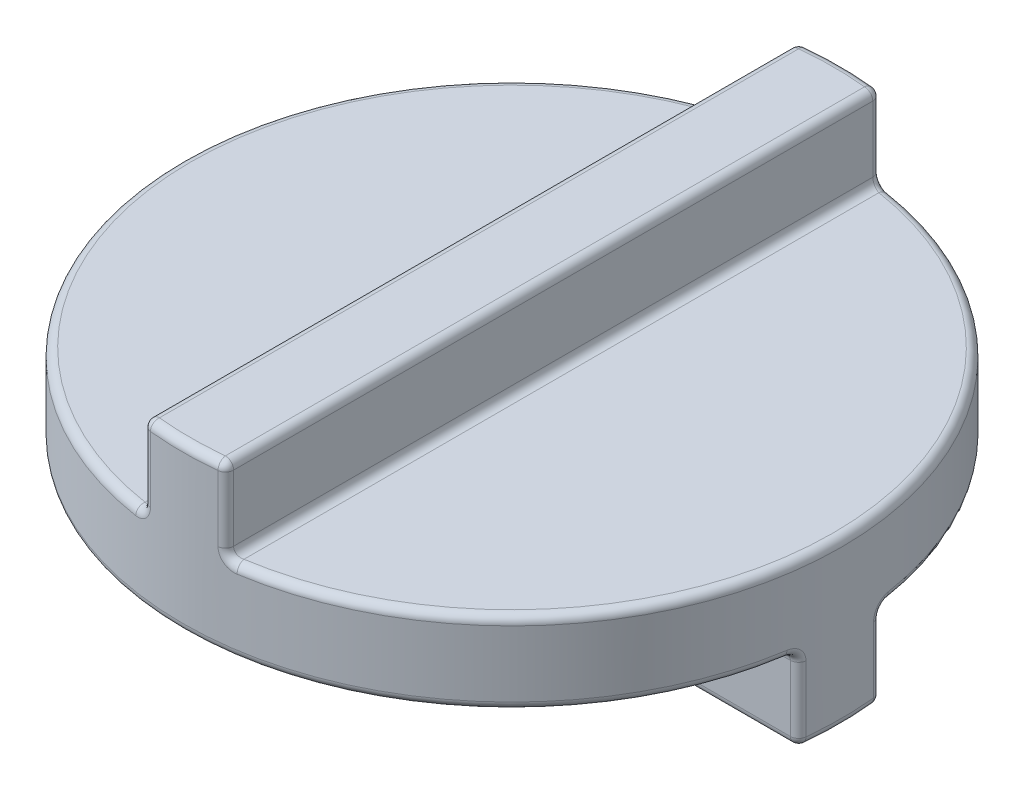
SolidWorks part; units mm, degrees
ref_plane "Front Plane" through (0, 0, 0) normal (1, 0, 0) x (0, 1, 0)
ref_plane "Top Plane" through (0, 0, 0) normal (0, 0, 1) x (0, 1, 0)
ref_plane "Right Plane" through (0, 0, 0) normal (0, 1, 0) x (-1, 0, 0)
sketch "Sketch2" plane through (0, 0, 0) normal (0, 1, 0) x (-1, 0, 0)
  circle A0 centre (0, 0) radius 60
  dimension "D1" = 120
extrude "Boss-Extrude1" add sketch "Sketch2" along normal mid plane 45
sketch "Sketch3" plane through (0, 22.5, 0) normal (0, 1, 0) x (-1, 0, 0)
  line L1 (-7.5, -65) -> (7.5, -65)
  line L2 (-7.5, -65) -> (-7.5, 65)
  line L3 (-7.5, 65) -> (7.5, 65)
  line L4 (7.5, -65) -> (7.5, 65)
  line L5 (-7.5, -65) -> (7.5, 65) construction
  line L6 (-7.5, 65) -> (7.5, -65) construction
  point P0 (0, 0)
  dimension "D1" = 15
  dimension "D2" = 130
extrude "Cut-Extrude1" cut sketch "Sketch3" against normal blind 15 flip side to cut
sketch "Sketch4" plane through (0, -22.5, 0) normal (0, -1, 0) x (1, 0, 0)
  line L1 (-65, 7.5) -> (65, 7.5)
  line L2 (-65, 7.5) -> (-65, -7.5)
  line L3 (-65, -7.5) -> (65, -7.5)
  line L4 (65, 7.5) -> (65, -7.5)
  line L5 (-65, 7.5) -> (65, -7.5) construction
  line L6 (-65, -7.5) -> (65, 7.5) construction
  point P0 (0, 0)
  dimension "D1" = 15
  dimension "D2" = 130
extrude "Cut-Extrude2" cut sketch "Sketch4" against normal blind 15 flip side to cut
fillet "Fillet1" radius 1.5 24 edges at (59.5294, -15, -7.5) (-59.5294, -15, -7.5) (-59.5294, -15, 7.5) (59.5294, -15, 7.5) (7.5, 15, 59.5294) (7.5, 15, -59.5294) (-7.5, 15, -59.5294) (-7.5, 15, 59.5294) (0, -7.5, -7.5) (0, -7.5, -60) (-60, -22.5, 0) (60, -22.5, 0) (0, -22.5, 7.5) (0, -22.5, -7.5) (0, -7.5, 7.5) (0, -7.5, 60) (7.5, 7.5, 0) (60, 7.5, 0) (7.5, 22.5, 0) (0, 22.5, -60) (0, 22.5, 60) (-7.5, 22.5, 0) (-7.5, 7.5, 0) (-60, 7.5, 0)
